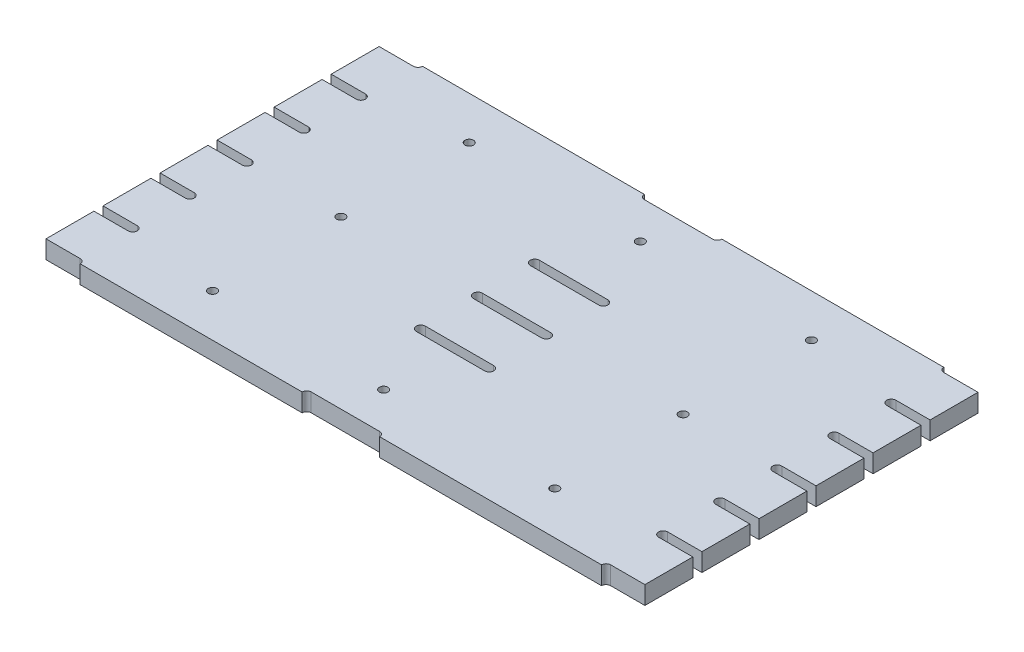
SolidWorks part; units mm, degrees
ref_plane "Front Plane" through (0, 0, 0) normal (0, 0, 1) x (1, 0, 0)
ref_plane "Top Plane" through (0, 0, 0) normal (0, 1, 0) x (1, 0, 0)
ref_plane "Right Plane" through (0, 0, 0) normal (1, 0, 0) x (0, 0, -1)
sketch "Sketch1" plane through (0, 0, 0) normal (0, 1, 0) x (1, 0, 0)
  line L1 (105, -60) -> (-105, -60)
  line L2 (105, -60) -> (105, 60)
  line L3 (105, 60) -> (-105, 60)
  line L4 (-105, -60) -> (-105, 60)
  line L5 (105, -60) -> (-105, 60) construction
  line L6 (105, 60) -> (-105, -60) construction
  point P0 (0, 0)
  dimension "D1" = 210
  dimension "D2" = 120
extrude "Boss-Extrude1" add sketch "Sketch1" along normal blind 6.35
sketch "Sketch3" plane through (0, 6.35, 0) normal (0, 1, 0) x (1, 0, 0)
  line L0 (12, 0) -> (-12, 0) construction
  line L1 (12, -1.6) -> (-12, -1.6)
  line L2 (12, 1.6) -> (-12, 1.6)
  arc A0 (12, -1.6) -> (12, 1.6) centre (12, 0) ccw
  arc A1 (-12, 1.6) -> (-12, -1.6) centre (-12, 0) ccw
  point P2 (0, 0)
  dimension "D1" = 3.2
  dimension "D2" = 24
extrude "Cut-Extrude1" cut sketch "Sketch3" against normal through all both and the other way through all
pattern_linear "LPattern1" count 4 spacing 20 along (0, 0, 1) count 4 spacing 20 along (0, 0, -1) of "Cut-Extrude1"
pattern_linear "LPattern2" count 2 spacing 105 along (1, 0, 0) count 2 spacing 105 along (-1, 0, 0) of "LPattern1", "Cut-Extrude1"
sketch "Sketch4" plane through (0, 6.35, 0) normal (0, 1, 0) x (1, 0, 0)
  circle A0 centre (0, 30) radius 2.1 construction
  circle A1 centre (0, -30) radius 2.1
  circle A2 centre (0, 50) radius 2.1 construction
  circle A3 centre (0, -50) radius 2.1 construction
  dimension "D5" = 4.2
  dimension "D1" = 30
  dimension "D2" = 20
  dimension "D3" = 30
  dimension "D4" = 20
extrude "Cut-Extrude2" [suppressed] cut sketch "Sketch4" against normal through all both and the other way through all
pattern_linear "LPattern3" [suppressed] count 4 spacing 25 count 4 spacing 25
sketch "Sketch5" plane through (0, 6.35, 0) normal (0, 1, 0) x (1, 0, 0)
  line L1 (60, -45) -> (-60, -45) construction
  line L2 (60, -45) -> (60, 45) construction
  line L3 (60, 45) -> (-60, 45) construction
  line L4 (-60, -45) -> (-60, 45) construction
  line L5 (60, -45) -> (-60, 45) construction
  line L6 (60, 45) -> (-60, -45) construction
  point P0 (0, 0)
  dimension "D1" = 90
  dimension "D2" = 120
sketch "Sketch6" plane through (0, 6.35, 0) normal (0, 1, 0) x (1, 0, 0)
  line L0 (60, 45) -> (-60, 45) construction
  line L1 (60, -45) -> (-60, -45) construction
  circle A0 centre (-60, 45) radius 1.5
  circle A1 centre (60, 45) radius 1.5
  circle A2 centre (60, -45) radius 1.5
  circle A3 centre (-60, -45) radius 1.5
  circle A4 centre (0, 45) radius 1.5
  circle A5 centre (0, -45) radius 1.5
  dimension "D1" = 3
  dimension "D2" = 3
  dimension "D3" = 3
  dimension "D4" = 3
  dimension "D5" = 3
  dimension "D6" = 3
extrude "Cut-Extrude3" cut sketch "Sketch6" against normal blind 10
sketch "Sketch7" plane through (0, 6.35, 0) normal (0, 1, 0) x (1, 0, 0)
  line L0 (-60, -45) -> (-60, 45) construction
  line L1 (60, -45) -> (60, 45) construction
  circle A0 centre (-60, 0) radius 1.5
  circle A1 centre (60, 0) radius 1.5
  dimension "D1" = 3
  dimension "D2" = 3
extrude "Cut-Extrude4" cut sketch "Sketch7" against normal blind 10
sketch "Sketch8" plane through (0, 6.35, 0) normal (0, 1, 0) x (1, 0, 0)
  line L0 (-12, 40) -> (12, 40) construction
  line L1 (-12, 42) -> (12, 42)
  line L2 (-12, 38) -> (12, 38)
  line L3 (-12, -40) -> (12, -40) construction
  line L4 (-12, -38) -> (12, -38)
  line L5 (-12, -42) -> (12, -42)
  arc A0 (-12, 42) -> (-12, 38) centre (-12, 40) ccw
  arc A1 (12, 38) -> (12, 42) centre (12, 40) ccw
  arc A2 (-12, -38) -> (-12, -42) centre (-12, -40) ccw
  arc A3 (12, -42) -> (12, -38) centre (12, -40) ccw
  point P2 (0, 40)
  point P9 (0, -40)
  dimension "D1" = 2
  dimension "D2" = 2
extrude "Boss-Extrude2" add sketch "Sketch8" against normal up to surface (6.35 mm away) up to face at (-60, 0, 1.5)
